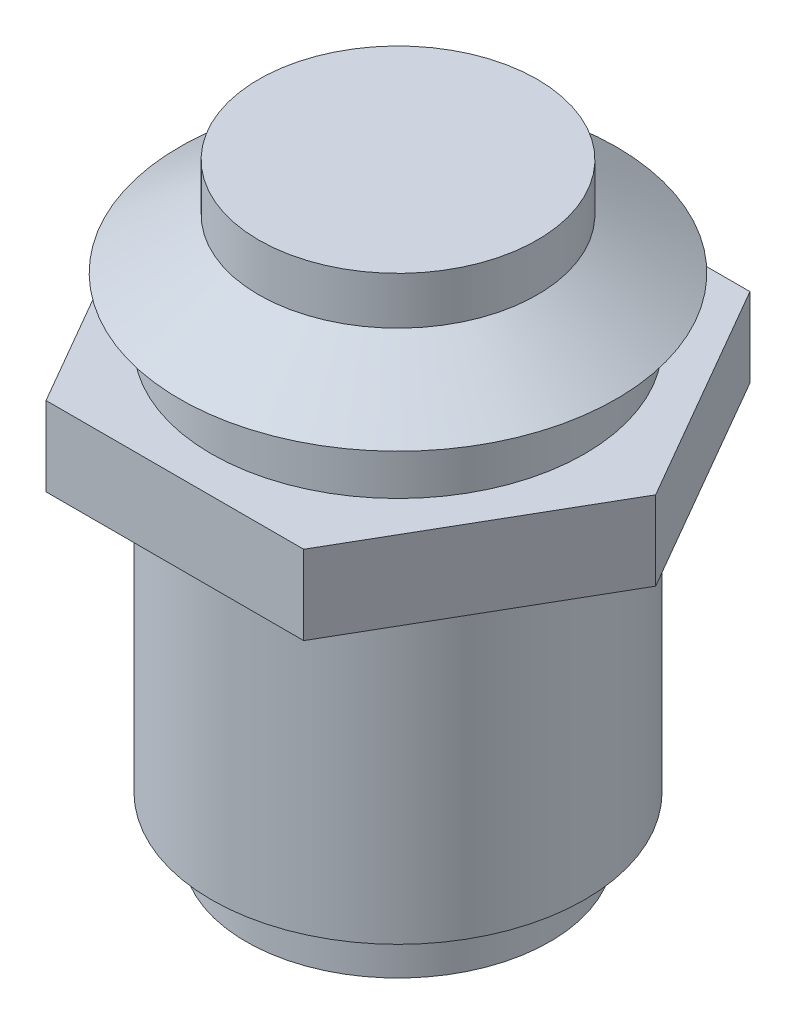
SolidWorks part; units mm, degrees
ref_plane "Front Plane" through (0, 0, 0) normal (0, 0, 1) x (1, 0, 0)
ref_plane "Top Plane" through (0, 0, 0) normal (0, 1, 0) x (1, 0, 0)
ref_plane "Right Plane" through (0, 0, 0) normal (1, 0, 0) x (0, 0, -1)
sketch "Sketch1" plane through (0, 0, 0) normal (1, 0, 0) x (0, 0, -1)
  line L0 (0, 0) -> (0, 25.0916) construction
  line L1 (0, 0) -> (0, 19)
  line L2 (0, 19) -> (4.4, 19)
  line L3 (4.4, 19) -> (4.4, 17.5)
  line L4 (4.4, 17.5) -> (6.9, 15.9)
  line L5 (6.9, 15.9) -> (5.9, 15.9)
  line L6 (5.9, 15.9) -> (5.9, 1.7)
  line L7 (5.9, 1.7) -> (4.8, 1.7)
  line L8 (4.8, 1.7) -> (4.8, 0)
  line L9 (4.8, 0) -> (0, 0)
  point P3 (4.8, 0.85)
  dimension "D1" = 19
  dimension "D2" = 8.8
  dimension "D3" = 1.5
  dimension "D4" = 13.8
  dimension "D5" = 1.6
  dimension "D6" = 11.8
  dimension "D7" = 9.6
  dimension "D8" = 1.7
revolve "Revolve1" add sketch "Sketch1" angle 360 about L0
sketch "Sketch2" plane through (0, 13.9, 0) normal (0, -1, 0) x (1, 0, 0)
  line L1 (-4.0703, -7.05) -> (4.0703, -7.05)
  line L2 (4.0703, -7.05) -> (8.1406, 0)
  line L3 (8.1406, 0) -> (4.0703, 7.05)
  line L4 (4.0703, 7.05) -> (-4.0703, 7.05)
  line L5 (-4.0703, 7.05) -> (-8.1406, 0)
  line L6 (-8.1406, 0) -> (-4.0703, -7.05)
  circle A0 centre (0, 0) radius 7.05 construction
  dimension "D1" = 14.1
extrude "Boss-Extrude1" add sketch "Sketch2" along normal blind 2.5 separate body
